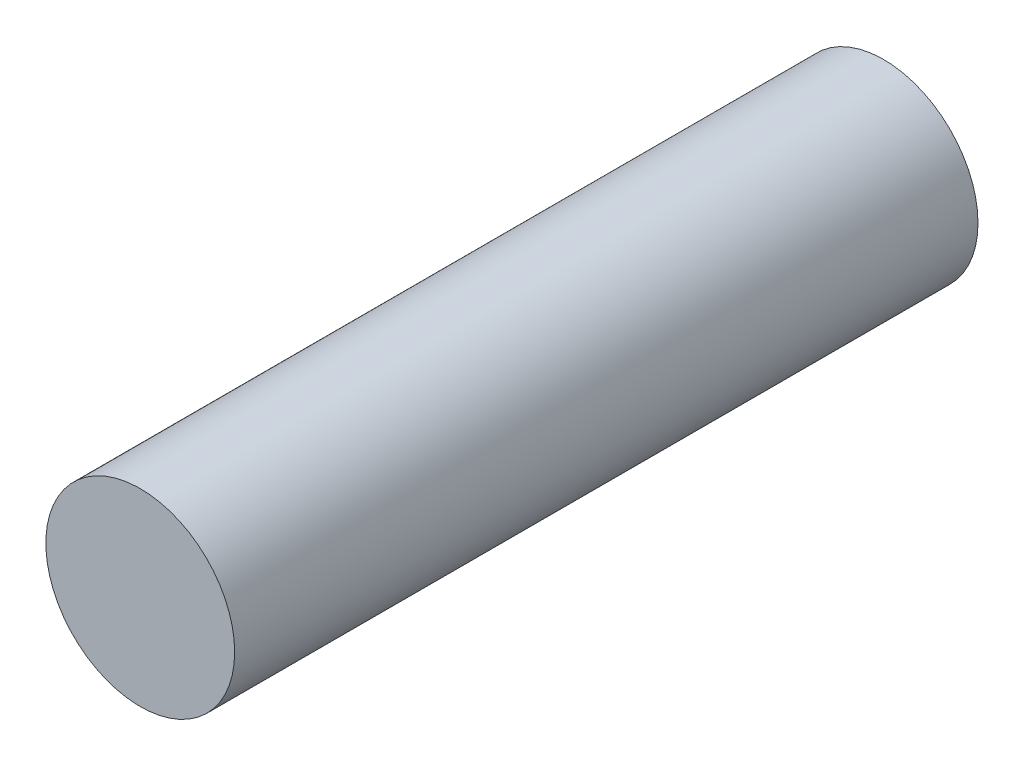
SolidWorks part; units mm, degrees
ref_plane "Front Plane" through (0, 0, 0) normal (0, 0, 1) x (1, 0, 0)
ref_plane "Top Plane" through (0, 0, 0) normal (0, 1, 0) x (1, 0, 0)
ref_plane "Right Plane" through (0, 0, 0) normal (1, 0, 0) x (0, 0, -1)
sketch "Sketch1" plane through (0, 0, 0) normal (0, 0, 1) x (1, 0, 0)
  circle A0 centre (0, 0) radius 12.7
  dimension "D1" = 25.4
extrude "Boss-Extrude1" add sketch "Sketch1" along normal blind 100
